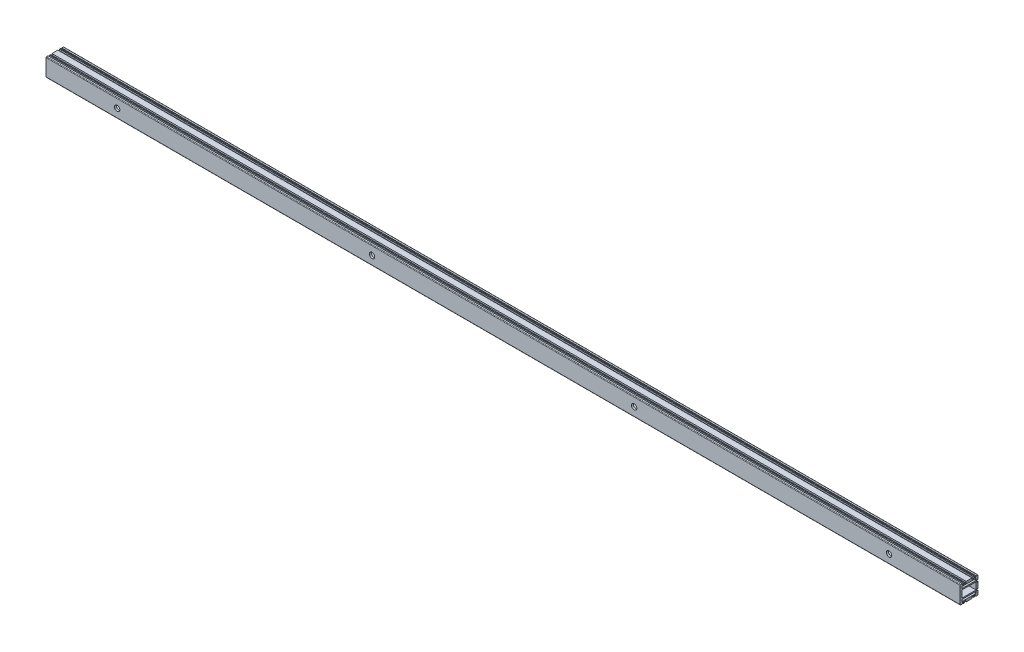
SolidWorks part; units mm, degrees
ref_plane "前视基准面" through (0, 0, 0) normal (0, 0, 1) x (1, 0, 0)
ref_plane "上视基准面" through (0, 0, 0) normal (0, 1, 0) x (1, 0, 0)
ref_plane "右视基准面" through (0, 0, 0) normal (1, 0, 0) x (0, 0, -1)
sketch "草图1" plane through (0, 0, 0) normal (1, 0, 0) x (0, 0, -1)
  line L0 (-15, 15) -> (15, -15) construction
  line L1 (-14, 15) -> (-11.5, 15)
  line L2 (-15, 14) -> (-15, -14)
  line L3 (-14, -15) -> (-11.5, -15)
  line L4 (15, 14) -> (15, 8)
  line L5 (15, 15) -> (-15, -15) construction
  line L6 (-11.5, 15) -> (-11.5, 13.5)
  line L7 (-11.5, 13.5) -> (-11.4, 13.5)
  line L8 (-11, 13.1) -> (-11, 12)
  line L9 (-11, 12) -> (-9.5, 12)
  line L10 (-9.5, 12) -> (-9.5, 15)
  line L11 (-9.5, 15) -> (-8, 15)
  line L12 (-8, 15) -> (-8, 12.5)
  line L13 (-8, 12.5) -> (-5, 12.5)
  line L14 (-5, 12.5) -> (-5, 15)
  line L15 (-5, 15) -> (5, 15)
  line L16 (0, 21.5201) -> (0, -18.309) construction
  line L17 (0, 55) -> (0, -55) construction
  line L18 (5, 12.5) -> (5, 15)
  line L19 (8, 12.5) -> (5, 12.5)
  line L20 (8, 15) -> (8, 12.5)
  line L21 (9.5, 15) -> (8, 15)
  line L22 (9.5, 12) -> (9.5, 15)
  line L23 (11, 12) -> (9.5, 12)
  line L24 (11, 13.1) -> (11, 12)
  line L25 (11.5, 13.5) -> (11.4, 13.5)
  line L26 (11.5, 15) -> (11.5, 13.5)
  line L27 (8, 15) -> (9.5, 15)
  line L28 (11.5, 15) -> (14, 15)
  line L29 (-19.8303, 0) -> (22.13, 0) construction
  line L30 (55, 0) -> (-55, 0) construction
  line L31 (8, -15) -> (9.5, -15)
  line L32 (11.5, -15) -> (11.5, -13.5)
  line L33 (11.5, -13.5) -> (11.4, -13.5)
  line L34 (11, -13.1) -> (11, -12)
  line L35 (11, -12) -> (9.5, -12)
  line L36 (9.5, -12) -> (9.5, -15)
  line L37 (9.5, -15) -> (8, -15)
  line L38 (8, -15) -> (8, -12.5)
  line L39 (8, -12.5) -> (5, -12.5)
  line L40 (5, -12.5) -> (5, -15)
  line L41 (-5, -15) -> (5, -15)
  line L42 (-5, -12.5) -> (-5, -15)
  line L43 (-8, -12.5) -> (-5, -12.5)
  line L44 (-8, -15) -> (-8, -12.5)
  line L45 (-9.5, -15) -> (-8, -15)
  line L46 (-9.5, -12) -> (-9.5, -15)
  line L47 (-11, -12) -> (-9.5, -12)
  line L48 (-11, -13.1) -> (-11, -12)
  line L49 (-11.5, -13.5) -> (-11.4, -13.5)
  line L50 (-11.5, -15) -> (-11.5, -13.5)
  line L51 (-9.5, -15) -> (-8, -15)
  line L52 (-5, -15) -> (5, -15)
  line L53 (8, -15) -> (9.5, -15)
  line L54 (11.5, -15) -> (14, -15)
  line L55 (15, 8) -> (12.5, 8)
  line L56 (12.5, 8) -> (12.5, 5)
  line L57 (12.5, 5) -> (15, 5)
  line L58 (12.5, -5) -> (15, -5)
  line L59 (12.5, -8) -> (12.5, -5)
  line L60 (15, -8) -> (12.5, -8)
  line L61 (15, 5) -> (15, -5)
  line L62 (15, -8) -> (15, -14)
  line L63 (12, -10.5) -> (12, -8.5)
  line L64 (-11.5, 11) -> (11.5, 11)
  line L65 (-12, 10.5) -> (-12, 8.5)
  line L66 (-11.5, 8) -> (11.5, 8)
  line L67 (12, 10.5) -> (12, 8.5)
  line L68 (-11.5, -8) -> (11.5, -8)
  line L69 (-12, -10.5) -> (-12, -8.5)
  line L70 (-11.5, -11) -> (11.5, -11)
  line L72 (-11.75, 6) -> (11.75, 6)
  line L73 (-11.75, 6) -> (-11.75, -6)
  line L74 (-11.75, -6) -> (11.75, -6)
  line L75 (11.75, 6) -> (11.75, -6)
  arc A0 (12, 8.5) -> (11.5, 8) centre (11.5, 8.5) cw
  arc A1 (11.5, 11) -> (12, 10.5) centre (11.5, 10.5) cw
  arc A2 (-11.5, 11) -> (-12, 10.5) centre (-11.5, 10.5) ccw
  arc A3 (-11.5, 8) -> (-12, 8.5) centre (-11.5, 8.5) cw
  arc A4 (-11, -13.1) -> (-11.4, -13.5) centre (-11.4, -13.1) cw
  arc A5 (11.4, -13.5) -> (11, -13.1) centre (11.4, -13.1) cw
  arc A6 (11.4, 13.5) -> (11, 13.1) centre (11.4, 13.1) ccw
  arc A7 (-11, 13.1) -> (-11.4, 13.5) centre (-11.4, 13.1) ccw
  arc A8 (-11.5, -8) -> (-12, -8.5) centre (-11.5, -8.5) ccw
  arc A9 (-11.5, -11) -> (-12, -10.5) centre (-11.5, -10.5) cw
  arc A10 (11.5, -11) -> (12, -10.5) centre (11.5, -10.5) ccw
  arc A11 (12, -8.5) -> (11.5, -8) centre (11.5, -8.5) ccw
  arc A12 (14, 15) -> (15, 14) centre (14, 14) cw
  arc A13 (14, -15) -> (15, -14) centre (14, -14) ccw
  arc A14 (-15, -14) -> (-14, -15) centre (-14, -14) ccw
  arc A15 (-15, 14) -> (-14, 15) centre (-14, 14) cw
  point P69 (12, 11)
  point P72 (-12, 11)
  point P77 (-11, -13.5)
  point P80 (11, -13.5)
  point P83 (11, 13.5)
  point P86 (-11, 13.5)
  point P99 (-12, -11)
  point P100 (12, -11)
  dimension "D17" = 0.5
  dimension "D18" = 0.4
  dimension "D21" = 1
  dimension "D1" = 3.5
  dimension "D2" = 1.5
  dimension "D3" = 0.5
  dimension "D4" = 1.5
  dimension "D5" = 3
  dimension "D6" = 30
  dimension "D7" = 30
  dimension "D8" = 1.5
  dimension "D9" = 2.5
  dimension "D10" = 3
  dimension "D11" = 2.5
  dimension "D12" = 7
  dimension "D13" = 3
  dimension "D14" = 4
  dimension "D15" = 3
  dimension "D16" = 24
  dimension "D19" = 23.5
  dimension "D20" = 12
extrude "凸台-拉伸1" add sketch "草图1" along normal mid plane 1542 contours A15 L2 A14 L3 L50 L49 A4 L48 L47 L46 L45 L44 L43 L42 L41 L40 L39 L38 L31 L36 L35 L34 A5 L33 L32 L54 A13 L62 L60 L59 L58 L61 L57 L56 L55 L4 A12 L28 L26 L25 A6 L24 L23 L22 L21 L20 L19 L18 L15 L14 L13
hole_wizard "M6 螺纹孔1" positions "草图3" profile "草图2" tap size "M6" standard "GB"
sketch "草图3" plane through (0, -15, 0) normal (0, -1, 0) x (1, 0, 0)
  line L0 (-771, 5) -> (-771, -5) construction
  line L1 (771, -15) -> (-771, -15) construction
  point P0 (-751, 0)
  point P1 (-736, 0)
  point P4 (-566, 0)
  point P7 (-551, 0)
  point P10 (-481, 0)
  point P13 (-466, 0)
  point P16 (94, 0)
  point P19 (109, 0)
  point P22 (179, 0)
  point P25 (194, 0)
  point P28 (736, 0)
  point P31 (751, 0)
  dimension "D1" = 20
  dimension "D2" = 15
sketch "草图2" plane through (-751, -15, 0) normal (1, 0, 0) x (0, 0, -1)
  line L0 (0, 0) -> (0, 16.5022)
  line L1 (0, 16.5022) -> (2.5, 15)
  line L2 (2.5, 15) -> (2.5, 0)
  line L5 (2.5, 0) -> (0, 0)
  line L10 (0, 16.5022) -> (-2.5, 15) construction
  line L11 (0, -6.35) -> (0, 107.95) construction
  dimension "螺纹孔钻头直径" = 5
  dimension "螺纹孔钻头深度" = 15
  dimension "导头角度" = 118
cosmetic thread "孔螺蚊线1" parameters "D1"=9, "D2"=6
cosmetic thread "孔螺蚊线2" parameters "D1"=9, "D2"=6
cosmetic thread "孔螺蚊线3" parameters "D1"=9, "D2"=6
cosmetic thread "孔螺蚊线4" parameters "D1"=9, "D2"=6
cosmetic thread "孔螺蚊线5" parameters "D1"=9, "D2"=6
cosmetic thread "孔螺蚊线6" parameters "D1"=9, "D2"=6
cosmetic thread "孔螺蚊线7" parameters "D1"=9, "D2"=6
cosmetic thread "孔螺蚊线8" parameters "D1"=9, "D2"=6
cosmetic thread "孔螺蚊线9" parameters "D1"=9, "D2"=6
cosmetic thread "孔螺蚊线10" parameters "D1"=9, "D2"=6
cosmetic thread "孔螺蚊线11" parameters "D1"=9, "D2"=6
cosmetic thread "孔螺蚊线12" parameters "D1"=9, "D2"=6
hole_wizard "M6 螺纹孔2" positions "草图5" profile "草图4" tap size "M6" standard "GB"
sketch "草图5" plane through (0, 0, -15) normal (0, 0, -1) x (-1, 0, 0)
  line L0 (771, 5) -> (771, -5) construction
  line L1 (-771, -15) -> (771, -15) construction
  point P0 (751, 0)
  point P1 (736, 0)
  point P4 (566, 0)
  point P7 (551, 0)
  point P10 (481, 0)
  point P13 (466, 0)
  point P16 (-481, 0)
  point P19 (-466, 0)
  point P22 (-551, 0)
  point P25 (-566, 0)
  point P28 (-751, 0)
  point P31 (-736, 0)
  dimension "D1" = 20
  dimension "D2" = 15
sketch "草图4" plane through (-751, 0, -15) normal (1, 0, 0) x (0, 1, 0)
  line L0 (0, 0) -> (0, 16.5022)
  line L1 (0, 16.5022) -> (2.5, 15)
  line L2 (2.5, 15) -> (2.5, 0)
  line L5 (2.5, 0) -> (0, 0)
  line L10 (0, 16.5022) -> (-2.5, 15) construction
  line L11 (0, -6.35) -> (0, 107.95) construction
  dimension "螺纹孔钻头直径" = 5
  dimension "螺纹孔钻头深度" = 15
  dimension "导头角度" = 118
cosmetic thread "孔螺蚊线13" parameters "D1"=3.25, "D2"=6
cosmetic thread "孔螺蚊线14" parameters "D1"=3.25, "D2"=6
cosmetic thread "孔螺蚊线15" parameters "D1"=3.25, "D2"=6
cosmetic thread "孔螺蚊线16" parameters "D1"=3.25, "D2"=6
cosmetic thread "孔螺蚊线17" parameters "D1"=3.25, "D2"=6
cosmetic thread "孔螺蚊线18" parameters "D1"=3.25, "D2"=6
cosmetic thread "孔螺蚊线19" parameters "D1"=3.25, "D2"=6
cosmetic thread "孔螺蚊线20" parameters "D1"=3.25, "D2"=6
cosmetic thread "孔螺蚊线21" parameters "D1"=3.25, "D2"=6
cosmetic thread "孔螺蚊线22" parameters "D1"=3.25, "D2"=6
cosmetic thread "孔螺蚊线23" parameters "D1"=3.25, "D2"=6
cosmetic thread "孔螺蚊线24" parameters "D1"=3.25, "D2"=6
sketch "草图6" plane through (0, 0, -15) normal (0, 0, -1) x (-1, 0, 0)
  circle A0 centre (-651, 0) radius 4.5
  circle A1 centre (-221, 0) radius 4.5
  circle A2 centre (221, 0) radius 4.5
  circle A3 centre (651, 0) radius 4.5
extrude "切除-拉伸1" cut sketch "草图6" against normal through all
hole_wizard "M4 螺纹孔1" positions "草图8" profile "草图7" tap size "M4" standard "GB"
sketch "草图8" plane through (0, -15, 0) normal (0, -1, 0) x (1, 0, 0)
  line L0 (771, 15) -> (-771, 15) construction
  line L1 (771, 14) -> (771, 11.5) construction
  point P0 (711, 0)
  point P1 (591, 0)
  point P3 (471, 0)
  point P5 (221, 0)
  dimension "D1" = 15
  dimension "D2" = 60
  dimension "D3" = 120
  dimension "D4" = 120
  dimension "D5" = 250
sketch "草图7" plane through (711, -15, 0) normal (1, 0, 0) x (0, 0, -1)
  line L0 (0, 0) -> (0, 11.0914)
  line L1 (0, 11.0914) -> (1.65, 10.1)
  line L2 (1.65, 10.1) -> (1.65, 0)
  line L5 (1.65, 0) -> (0, 0)
  line L10 (0, 11.0914) -> (-1.65, 10.1) construction
  line L11 (0, -6.35) -> (0, 107.95) construction
  dimension "螺纹孔钻头直径" = 3.3
  dimension "螺纹孔钻头深度" = 10.1
  dimension "导头角度" = 118
cosmetic thread "孔螺蚊线25" parameters "D1"=8, "D2"=4
cosmetic thread "孔螺蚊线26" parameters "D1"=8, "D2"=4
cosmetic thread "孔螺蚊线27" parameters "D1"=8, "D2"=4
cosmetic thread "孔螺蚊线28" parameters "D1"=8, "D2"=4
hole_wizard "M6 螺纹孔3" positions "草图10" profile "草图9" tap size "M6" standard "GB"
sketch "草图10" plane through (0, -15, 0) normal (0, -1, 0) x (1, 0, 0)
  line L0 (771, -15) -> (-771, -15) construction
  line L1 (-771, 5) -> (-771, -5) construction
  point P1 (-221, 0)
  dimension "D1" = 15
  dimension "D2" = 550
sketch "草图9" plane through (-221, -15, 0) normal (1, 0, 0) x (0, 0, -1)
  line L0 (0, 0) -> (0, 16.5022)
  line L1 (0, 16.5022) -> (2.5, 15)
  line L2 (2.5, 15) -> (2.5, 0)
  line L5 (2.5, 0) -> (0, 0)
  line L10 (0, 16.5022) -> (-2.5, 15) construction
  line L11 (0, -6.35) -> (0, 107.95) construction
  dimension "螺纹孔钻头直径" = 5
  dimension "螺纹孔钻头深度" = 15
  dimension "导头角度" = 118
cosmetic thread "孔螺蚊线29" parameters "D1"=9, "D2"=6
